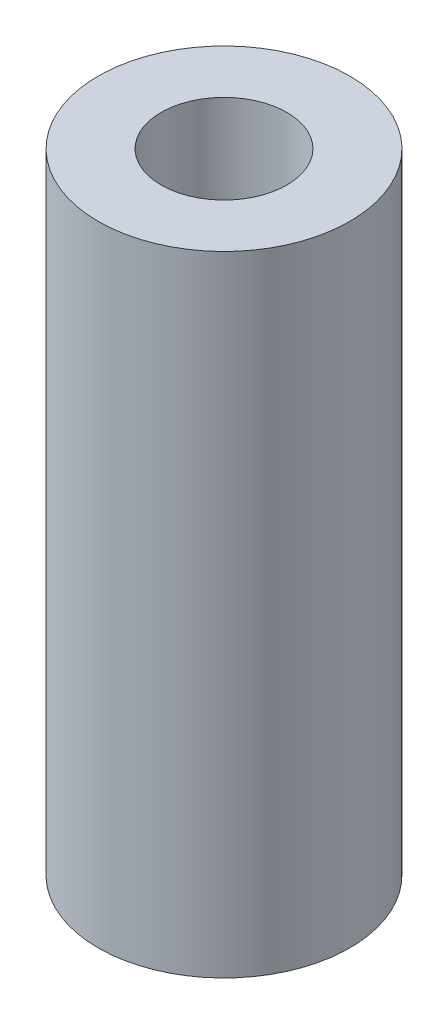
SolidWorks part; units mm, degrees
ref_plane "Front Plane" through (0, 0, 0) normal (0, 0, 1) x (1, 0, 0)
ref_plane "Top Plane" through (0, 0, 0) normal (0, 1, 0) x (1, 0, 0)
ref_plane "Right Plane" through (0, 0, 0) normal (1, 0, 0) x (0, 0, -1)
sketch "Sketch1" plane through (0, 0, 0) normal (0, 1, 0) x (1, 0, 0)
  circle A0 centre (0, 0) radius 6
  circle A1 centre (0, 0) radius 3
  dimension "D1" = 12
  dimension "D2" = 6
extrude "Boss-Extrude1" add sketch "Sketch1" along normal blind 30
